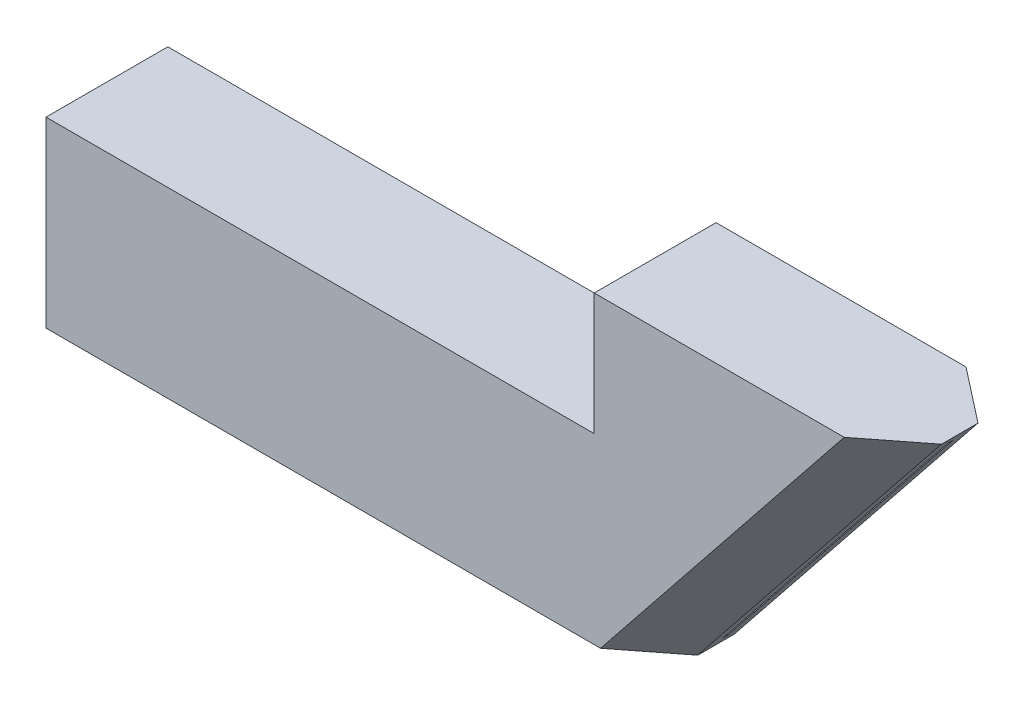
SolidWorks part; units mm, degrees
ref_plane "Front Plane" through (0, 0, 0) normal (0, 0, 1) x (1, 0, 0)
ref_plane "Top Plane" through (0, 0, 0) normal (0, 1, 0) x (1, 0, 0)
ref_plane "Right Plane" through (0, 0, 0) normal (1, 0, 0) x (0, 0, -1)
sketch "Sketch6" plane through (0, 0, 0) normal (0, 0, 1) x (1, 0, 0)
  line L0 (0, 0) -> (0, 76.2)
  line L1 (0, 76.2) -> (228.6, 76.2)
  line L2 (228.6, 76.2) -> (228.6, 127)
  line L3 (228.6, 127) -> (355.6, 127)
  line L4 (355.6, 127) -> (254, 0)
  line L5 (254, 0) -> (0, 0)
  dimension "D1" = 254
  dimension "D2" = 76.2
  dimension "D3" = 127
  dimension "D4" = 127
  dimension "D5" = 228.6
extrude "Boss-Extrude1" add sketch "Sketch6" along normal blind 50.8 contours L1 L2 L3 L4 L5 L0
chamfer "Chamfer2" distance 17.78 angle 45 1 edges at (304.8, 63.5, 50.8)
chamfer "Chamfer3" distance 17.78 angle 45 1 edges at (304.8, 63.5, 0)
ref_plane "Plane4" through (154.878, -123.9024, 0) normal (0.7809, -0.6247, 0) x (0, 0, -1)
sketch "Sketch8" plane through (154.878, -123.9024, 0) normal (0.7809, -0.6247, 0) x (0, 0, -1)
  line L0 (-24.384, 165.0225) -> (-17.78, 165.0225) construction
  line L1 (-26.416, 165.0225) -> (-24.384, 165.0225)
  line L2 (-26.416, 165.0225) -> (-26.416, 314.9619)
  line L3 (-26.416, 314.9619) -> (-24.384, 314.9619)
  line L4 (-24.384, 165.0225) -> (-24.384, 314.9619)
  line L5 (-17.78, 158.6725) -> (-17.78, 321.3119) construction
  line L6 (-26.416, 165.0225) -> (-33.02, 165.0225) construction
  line L7 (-33.02, 321.3119) -> (-33.02, 158.6725) construction
  line L8 (-26.416, 165.0225) -> (-26.416, 158.6725) construction
  line L9 (-33.02, 158.6725) -> (-17.78, 158.6725) construction
  line L10 (-24.384, 314.9619) -> (-24.384, 321.3119) construction
  line L11 (-33.02, 321.3119) -> (-17.78, 321.3119) construction
  dimension "D1" = 2.032
  dimension "D2" = 6.35
  dimension "D3" = 6.35
extrude "Cut-Extrude3" cut sketch "Sketch8" against normal blind 6.35
